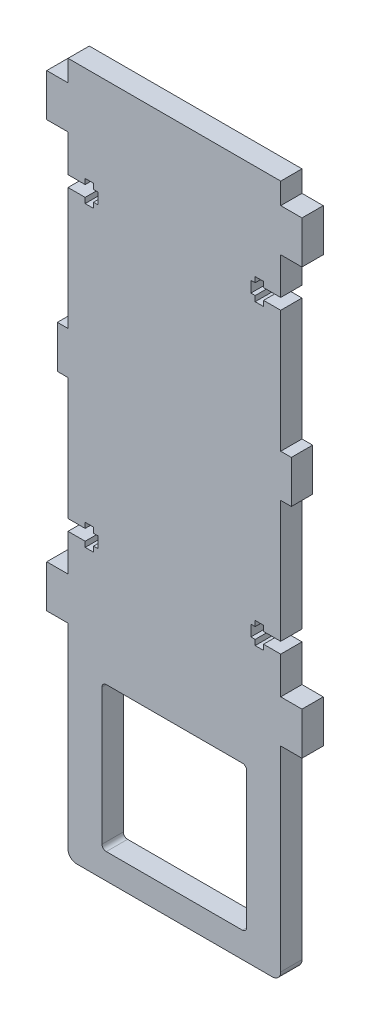
SolidWorks part; units mm, degrees
ref_plane "Front Plane" through (0, 0, 0) normal (0, 0, 1) x (1, 0, 0)
ref_plane "Top Plane" through (0, 0, 0) normal (0, 1, 0) x (1, 0, 0)
ref_plane "Right Plane" through (0, 0, 0) normal (1, 0, 0) x (0, 0, -1)
sketch "Sketch1" plane through (0, 0, 0) normal (0, 0, 1) x (1, 0, 0)
  line L1 (0, 0) -> (63.5, 0)
  line L2 (0, 0) -> (0, 152.4)
  line L3 (0, 152.4) -> (63.5, 152.4)
  line L4 (63.5, 0) -> (63.5, 152.4)
  dimension "D1" = 152.4
  dimension "D2" = 63.5
extrude "Boss-Extrude1" add sketch "Sketch1" along normal blind 6.35
sketch "Sketch2" plane through (0, 0, 6.35) normal (0, 0, 1) x (1, 0, 0)
  line L0 (0, 76.2) -> (63.5, 76.2) construction
  line L1 (0, 146.05) -> (-6.35, 146.05)
  line L2 (0, 146.05) -> (0, 133.35)
  line L3 (0, 133.35) -> (-6.35, 133.35)
  line L4 (-6.35, 146.05) -> (-6.35, 133.35)
  line L5 (0, 6.35) -> (-6.35, 6.35)
  line L6 (0, 6.35) -> (0, 19.05)
  line L7 (0, 19.05) -> (-6.35, 19.05)
  line L8 (-6.35, 6.35) -> (-6.35, 19.05)
  line L9 (0, 152.4) -> (0, 0) construction
  line L10 (63.5, 0) -> (63.5, 152.4) construction
  line L11 (-3.175, 76.2) -> (0, 76.2) construction
  line L12 (0, 82.55) -> (-3.175, 82.55)
  line L13 (0, 82.55) -> (0, 69.85)
  line L14 (0, 69.85) -> (-3.175, 69.85)
  line L15 (-3.175, 82.55) -> (-3.175, 69.85)
  line L16 (31.75, 152.4) -> (31.75, 0) construction
  line L17 (63.5, 152.4) -> (0, 152.4) construction
  line L18 (0, 0) -> (63.5, 0) construction
  line L19 (69.85, 146.05) -> (69.85, 133.35)
  line L20 (63.5, 133.35) -> (69.85, 133.35)
  line L21 (63.5, 146.05) -> (63.5, 133.35)
  line L22 (63.5, 146.05) -> (69.85, 146.05)
  line L23 (0, 82.55) -> (-3.175, 82.55)
  line L24 (0, 69.85) -> (-3.175, 69.85)
  line L25 (0, 82.55) -> (-3.175, 82.55)
  line L26 (0, 69.85) -> (-3.175, 69.85)
  line L27 (0, 82.55) -> (-3.175, 82.55)
  line L28 (0, 69.85) -> (-3.175, 69.85)
  line L29 (69.85, 6.35) -> (69.85, 19.05)
  line L30 (63.5, 19.05) -> (69.85, 19.05)
  line L31 (63.5, 6.35) -> (63.5, 19.05)
  line L32 (63.5, 6.35) -> (69.85, 6.35)
  line L33 (0, 82.55) -> (-3.175, 82.55)
  line L34 (0, 69.85) -> (-3.175, 69.85)
  line L35 (0, 82.55) -> (-3.175, 82.55)
  line L36 (0, 69.85) -> (-3.175, 69.85)
  line L37 (0, 82.55) -> (-3.175, 82.55)
  line L38 (0, 69.85) -> (-3.175, 69.85)
  line L39 (0, 82.55) -> (-3.175, 82.55)
  line L40 (0, 69.85) -> (-3.175, 69.85)
  line L41 (66.675, 76.2) -> (63.5, 76.2) construction
  line L42 (63.5, 69.85) -> (66.675, 69.85)
  line L43 (63.5, 82.55) -> (66.675, 82.55)
  line L44 (63.5, 69.85) -> (66.675, 69.85)
  line L45 (63.5, 82.55) -> (66.675, 82.55)
  line L46 (63.5, 69.85) -> (66.675, 69.85)
  line L47 (63.5, 82.55) -> (66.675, 82.55)
  line L48 (63.5, 69.85) -> (66.675, 69.85)
  line L49 (63.5, 82.55) -> (66.675, 82.55)
  line L50 (63.5, 69.85) -> (66.675, 69.85)
  line L51 (63.5, 82.55) -> (66.675, 82.55)
  line L52 (63.5, 69.85) -> (66.675, 69.85)
  line L53 (63.5, 82.55) -> (66.675, 82.55)
  line L54 (63.5, 69.85) -> (66.675, 69.85)
  line L55 (63.5, 82.55) -> (66.675, 82.55)
  line L56 (66.675, 82.55) -> (66.675, 69.85)
  line L57 (63.5, 69.85) -> (66.675, 69.85)
  line L58 (63.5, 82.55) -> (63.5, 69.85)
  line L59 (63.5, 82.55) -> (66.675, 82.55)
  line L60 (0, 152.4) -> (0, 0) construction
  line M1 (0, 152.4) -> (0, 0)
  line M3 (63.5, 0) -> (63.5, 152.4)
  dimension "D1" = 6.35
  dimension "D2" = 12.7
  dimension "D3" = 12.7
  dimension "D4" = 12.7
  dimension "D5" = 3.175
  dimension "D6" = 6.35
  dimension "D7" = 6.35
extrude "Boss-Extrude3" add sketch "Sketch2" against normal blind 6.35 contours L12 L15 L14 M1 | L22 L20 L19 M3 | L56 L43 L42 M3 | L32 L29 L30 M3 | L8 L5 L7 M1 | L4 L3 L2 L1
sketch "Sketch4" plane through (0, 0, 6.35) normal (0, 0, 1) x (1, 0, 0)
  line L0 (31.75, 152.4) -> (31.75, 0) construction
  line L1 (63.5, 152.4) -> (0, 152.4) construction
  line L2 (0, 0) -> (63.5, 0) construction
  line L3 (0, 133.35) -> (0, 82.55) construction
  line L4 (0, 122.301) -> (8.89, 122.301)
  line L5 (0, 122.301) -> (0, 118.999)
  line L6 (0, 118.999) -> (8.89, 118.999)
  line L7 (8.89, 122.301) -> (8.89, 118.999)
  line L8 (5.12, 120.65) -> (7.62, 120.65) construction
  line L9 (5.12, 123.9) -> (7.62, 123.9)
  line L10 (5.12, 123.9) -> (5.12, 117.4)
  line L11 (5.12, 117.4) -> (7.62, 117.4)
  line L12 (7.62, 123.9) -> (7.62, 117.4)
  line L13 (0, 120.65) -> (8.89, 120.65) construction
  line L14 (0, 133.35) -> (-6.35, 133.35) construction
  line L15 (-3.175, 76.2) -> (66.675, 76.2) construction
  line L16 (-3.175, 82.55) -> (-3.175, 69.85) construction
  line L17 (66.675, 82.55) -> (66.675, 69.85) construction
  line L18 (0, 31.75) -> (8.89, 31.75) construction
  line L19 (5.12, 31.75) -> (7.62, 31.75) construction
  line L20 (7.62, 28.5) -> (7.62, 35)
  line L21 (5.12, 35) -> (7.62, 35)
  line L22 (5.12, 28.5) -> (5.12, 35)
  line L23 (5.12, 28.5) -> (7.62, 28.5)
  line L24 (8.89, 30.099) -> (8.89, 33.401)
  line L25 (0, 33.401) -> (8.89, 33.401)
  line L26 (0, 30.099) -> (0, 33.401)
  line L27 (0, 30.099) -> (8.89, 30.099)
  line L28 (58.38, 31.75) -> (55.88, 31.75) construction
  line L29 (63.5, 31.75) -> (54.61, 31.75) construction
  line L30 (63.5, 120.65) -> (54.61, 120.65) construction
  line L31 (58.38, 120.65) -> (55.88, 120.65) construction
  line L32 (63.5, 30.099) -> (54.61, 30.099)
  line L33 (63.5, 30.099) -> (63.5, 33.401)
  line L34 (63.5, 33.401) -> (54.61, 33.401)
  line L35 (54.61, 30.099) -> (54.61, 33.401)
  line L36 (58.38, 28.5) -> (55.88, 28.5)
  line L37 (58.38, 28.5) -> (58.38, 35)
  line L38 (58.38, 35) -> (55.88, 35)
  line L39 (55.88, 28.5) -> (55.88, 35)
  line L40 (55.88, 123.9) -> (55.88, 117.4)
  line L41 (58.38, 117.4) -> (55.88, 117.4)
  line L42 (58.38, 123.9) -> (58.38, 117.4)
  line L43 (58.38, 123.9) -> (55.88, 123.9)
  line L44 (54.61, 122.301) -> (54.61, 118.999)
  line L45 (63.5, 118.999) -> (54.61, 118.999)
  line L46 (63.5, 122.301) -> (63.5, 118.999)
  line L47 (63.5, 122.301) -> (54.61, 122.301)
  dimension "D1" = 3.302
  dimension "D2" = 6.5
  dimension "D3" = 2.5
  dimension "D4" = 1.27
  dimension "D5" = 8.89
  dimension "D6" = 12.7
extrude "Cut-Extrude4" cut sketch "Sketch4" against normal blind 6.35 contours L6 L7 L4 L5 | L9 L12 L11 L10 | L21 L20 L23 L22 | L24 L25 L26 L27 | L35 L34 L33 L32 | L38 L39 L36 L37 | L41 L40 L43 L42 | L45 L44 L47 L46
sketch "Sketch5" plane through (0, 0, 6.35) normal (0, 0, 1) x (1, 0, 0)
  line L0 (0, 0) -> (63.5, 0) construction
  line L1 (0, 0) -> (63.5, 0)
  line L2 (0, 0) -> (0, -50.8)
  line L3 (0, -50.8) -> (63.5, -50.8)
  line L4 (63.5, 0) -> (63.5, -50.8)
  line L5 (31.75, 0) -> (31.75, -50.8) construction
  line L6 (0, -25.4) -> (63.5, -25.4) construction
  line L8 (10.16, -3.81) -> (53.34, -3.81)
  line L9 (10.16, -3.81) -> (10.16, -46.99)
  line L10 (10.16, -46.99) -> (53.34, -46.99)
  line L11 (53.34, -3.81) -> (53.34, -46.99)
  line L12 (10.16, -3.81) -> (53.34, -46.99) construction
  line L13 (10.16, -46.99) -> (53.34, -3.81) construction
  point P12 (31.75, -25.4)
  dimension "D1" = 50.8
  dimension "D2" = 43.18
  dimension "D3" = 43.18
extrude "Boss-Extrude4" add sketch "Sketch5" against normal blind 6.35
sketch "Sketch7" plane through (0, 0, 6.35) normal (0, 0, 1) x (1, 0, 0)
  line L0 (63.5, -50.8) -> (63.5, 6.35) construction
  line L1 (0, -50.8) -> (63.5, -50.8)
  line L2 (0, -50.8) -> (0, -54.61)
  line L3 (0, -54.61) -> (63.5, -54.61)
  line L4 (63.5, -50.8) -> (63.5, -54.61)
  dimension "D1" = 3.81
extrude "Boss-Extrude5" add sketch "Sketch7" against normal blind 6.35
fillet "Fillet1" radius 2.54 2 edges at (63.5, -54.61, 3.175) (0, -54.61, 3.175)
fillet "Fillet2" radius 1.27 4 edges at (53.34, -46.99, 3.175) (53.34, -3.81, 3.175) (10.16, -3.81, 3.175) (10.16, -46.99, 3.175)
